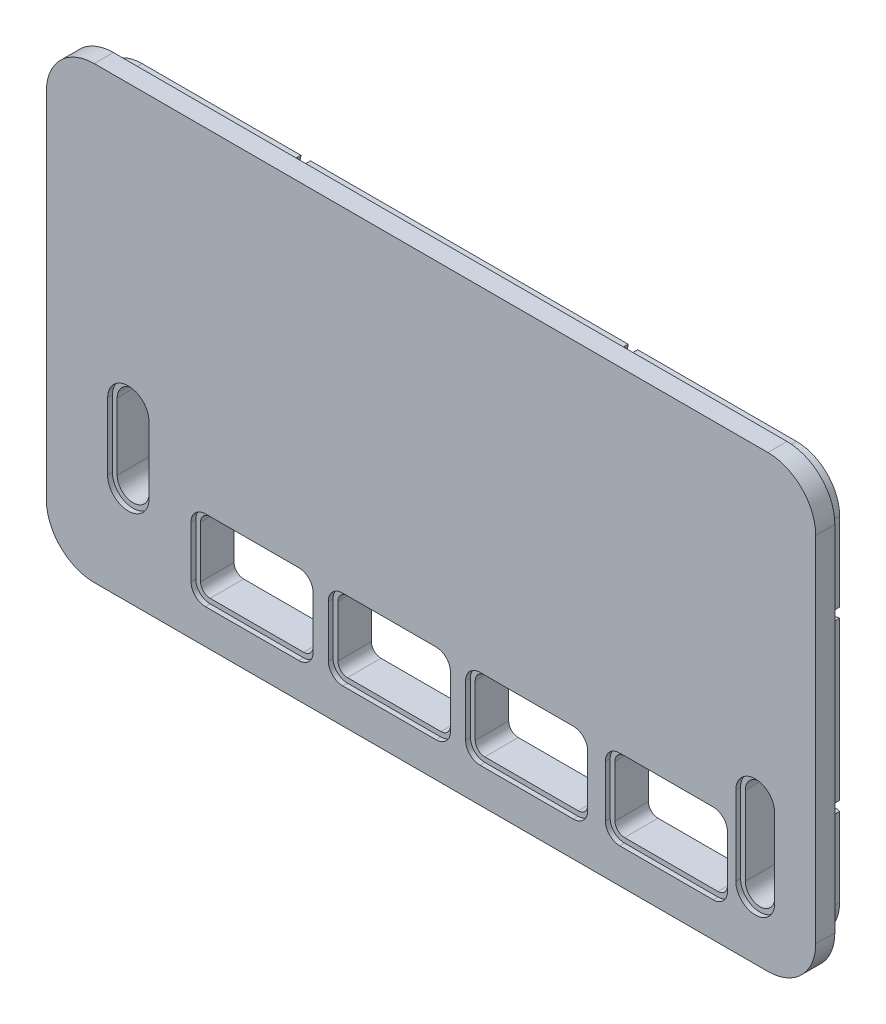
SolidWorks part; units mm, degrees
ref_plane "前视基准面" through (0, 0, 0) normal (0, 0, 1) x (1, 0, 0)
ref_plane "上视基准面" through (0, 0, 0) normal (0, 1, 0) x (1, 0, 0)
ref_plane "右视基准面" through (0, 0, 0) normal (1, 0, 0) x (0, 0, -1)
other "Configuration Table"
ref_plane "基准面1" through (0, 0, 994.7617) normal (0, 0, 1) x (1, 0, 0)
sketch "草图1" plane through (0, 0, 994.7617) normal (0, 0, 1) x (1, 0, 0)
  line L4 (-36.9772, -23.153) -> (-20.3758, -23.153)
  line L5 (35.9285, -18.653) -> (35.9285, -10.4094)
  line L6 (31.4285, 20.8216) -> (14.8271, 20.8216)
  line L7 (-41.4772, 16.3216) -> (-41.4772, 8.078)
  line L8 (-36.9772, -23.153) -> (-20.3758, -23.153)
  line L9 (35.9285, -18.653) -> (35.9285, -10.4094)
  line L10 (31.4285, 20.8216) -> (14.8271, 20.8216)
  line L11 (-41.4772, 16.3216) -> (-41.4772, 8.078)
  line L84 (35.9285, 8.078) -> (35.9285, 16.3216)
  line L85 (35.9285, 8.078) -> (35.9285, 16.3216)
  line L86 (-20.3758, 20.8216) -> (-36.9772, 20.8216)
  line L87 (-20.3758, 20.8216) -> (-36.9772, 20.8216)
  line L88 (-41.4772, -10.4094) -> (-41.4772, -18.653)
  line L89 (-41.4772, -10.4094) -> (-41.4772, -18.653)
  line L90 (14.8271, -23.153) -> (31.4285, -23.153)
  line L91 (14.8271, -23.153) -> (31.4285, -23.153)
  line L92 (15.3271, 19.8216) -> (13.3271, 19.8216)
  line L93 (15.3271, 19.8216) -> (13.3271, 19.8216)
  line L94 (13.8271, 20.8216) -> (-19.3758, 20.8216)
  line L95 (13.8271, 20.8216) -> (-19.3758, 20.8216)
  line L96 (-18.8758, 19.8216) -> (-20.8758, 19.8216)
  line L97 (-18.8758, 19.8216) -> (-20.8758, 19.8216)
  line L98 (-40.6203, 8.578) -> (-40.6203, 6.578)
  line L99 (-40.6203, 8.578) -> (-40.6203, 6.578)
  line L100 (-41.4772, 7.078) -> (-41.4772, -9.4094)
  line L101 (-41.4772, 7.078) -> (-41.4772, -9.4094)
  line L102 (-40.6203, -8.9094) -> (-40.6203, -10.9094)
  line L103 (-40.6203, -8.9094) -> (-40.6203, -10.9094)
  line L104 (-20.8758, -22.153) -> (-18.8758, -22.153)
  line L105 (-20.8758, -22.153) -> (-18.8758, -22.153)
  line L106 (-19.3758, -23.153) -> (13.8271, -23.153)
  line L107 (-19.3758, -23.153) -> (13.8271, -23.153)
  line L108 (13.3271, -22.153) -> (15.3271, -22.153)
  line L109 (13.3271, -22.153) -> (15.3271, -22.153)
  line L110 (35.0716, -10.9094) -> (35.0716, -8.9094)
  line L111 (35.0716, -10.9094) -> (35.0716, -8.9094)
  line L112 (35.9285, -9.4094) -> (35.9285, 7.078)
  line L113 (35.9285, -9.4094) -> (35.9285, 7.078)
  line L114 (35.0716, 6.578) -> (35.0716, 8.578)
  line L115 (35.0716, 6.578) -> (35.0716, 8.578)
  arc A4 (-41.4772, -18.653) -> (-36.9772, -23.153) centre (-36.9772, -18.653) ccw
  arc A5 (31.4285, -23.153) -> (35.9285, -18.653) centre (31.4285, -18.653) ccw
  arc A6 (35.9285, 16.3216) -> (31.4285, 20.8216) centre (31.4285, 16.3216) ccw
  arc A7 (-36.9772, 20.8216) -> (-41.4772, 16.3216) centre (-36.9772, 16.3216) ccw
  arc A8 (-41.4772, -18.653) -> (-36.9772, -23.153) centre (-36.9772, -18.653) ccw
  arc A9 (31.4285, -23.153) -> (35.9285, -18.653) centre (31.4285, -18.653) ccw
  arc A10 (35.9285, 16.3216) -> (31.4285, 20.8216) centre (31.4285, 16.3216) ccw
  arc A11 (-36.9772, 20.8216) -> (-41.4772, 16.3216) centre (-36.9772, 16.3216) ccw
  arc A84 (14.8271, 20.8216) -> (15.3271, 19.8216) centre (16.0771, 20.8216) ccw
  arc A85 (14.8271, 20.8216) -> (15.3271, 19.8216) centre (16.0771, 20.8216) ccw
  arc A86 (13.3271, 19.8216) -> (13.8271, 20.8216) centre (12.5771, 20.8216) ccw
  arc A87 (13.3271, 19.8216) -> (13.8271, 20.8216) centre (12.5771, 20.8216) ccw
  arc A88 (-19.3758, 20.8216) -> (-18.8758, 19.8216) centre (-18.1258, 20.8216) ccw
  arc A89 (-19.3758, 20.8216) -> (-18.8758, 19.8216) centre (-18.1258, 20.8216) ccw
  arc A90 (-20.8758, 19.8216) -> (-20.3758, 20.8216) centre (-21.6258, 20.8216) ccw
  arc A91 (-20.8758, 19.8216) -> (-20.3758, 20.8216) centre (-21.6258, 20.8216) ccw
  arc A92 (-41.4772, 8.078) -> (-40.6203, 8.578) centre (-41.1946, 8.578) ccw
  arc A93 (-41.4772, 8.078) -> (-40.6203, 8.578) centre (-41.1946, 8.578) ccw
  arc A94 (-40.6203, 6.578) -> (-41.4772, 7.078) centre (-41.4772, 6.0937) ccw
  arc A95 (-40.6203, 6.578) -> (-41.4772, 7.078) centre (-41.4772, 6.0937) ccw
  arc A96 (-41.4772, -9.4094) -> (-40.6203, -8.9094) centre (-41.4772, -8.4251) ccw
  arc A97 (-41.4772, -9.4094) -> (-40.6203, -8.9094) centre (-41.4772, -8.4251) ccw
  arc A98 (-40.6203, -10.9094) -> (-41.4772, -10.4094) centre (-41.1946, -10.9094) ccw
  arc A99 (-40.6203, -10.9094) -> (-41.4772, -10.4094) centre (-41.1946, -10.9094) ccw
  arc A100 (-20.3758, -23.153) -> (-20.8758, -22.153) centre (-21.6258, -23.153) ccw
  arc A101 (-20.3758, -23.153) -> (-20.8758, -22.153) centre (-21.6258, -23.153) ccw
  arc A102 (-18.8758, -22.153) -> (-19.3758, -23.153) centre (-18.1258, -23.153) ccw
  arc A103 (-18.8758, -22.153) -> (-19.3758, -23.153) centre (-18.1258, -23.153) ccw
  arc A104 (13.8271, -23.153) -> (13.3271, -22.153) centre (12.5771, -23.153) ccw
  arc A105 (13.8271, -23.153) -> (13.3271, -22.153) centre (12.5771, -23.153) ccw
  arc A106 (15.3271, -22.153) -> (14.8271, -23.153) centre (16.0771, -23.153) ccw
  arc A107 (15.3271, -22.153) -> (14.8271, -23.153) centre (16.0771, -23.153) ccw
  arc A108 (35.9285, -10.4094) -> (35.0716, -10.9094) centre (35.6459, -10.9094) ccw
  arc A109 (35.9285, -10.4094) -> (35.0716, -10.9094) centre (35.6459, -10.9094) ccw
  arc A110 (35.0716, -8.9094) -> (35.9285, -9.4094) centre (35.9285, -8.4251) ccw
  arc A111 (35.0716, -8.9094) -> (35.9285, -9.4094) centre (35.9285, -8.4251) ccw
  arc A112 (35.9285, 7.078) -> (35.0716, 6.578) centre (35.9285, 6.0937) ccw
  arc A113 (35.9285, 7.078) -> (35.0716, 6.578) centre (35.9285, 6.0937) ccw
  arc A114 (35.0716, 8.578) -> (35.9285, 8.078) centre (35.6459, 8.578) ccw
  arc A115 (35.0716, 8.578) -> (35.9285, 8.078) centre (35.6459, 8.578) ccw
  dimension "D1" = 0
extrude "凸台-拉伸1" add sketch "草图1" along normal blind 2
sketch "草图2" plane through (0, 0, 996.7617) normal (0, 0, 1) x (1, 0, 0)
  line L4 (-42.9772, 17.3216) -> (-42.9772, -19.653)
  line L5 (-37.9772, -24.653) -> (32.4285, -24.653)
  line L6 (37.4285, -19.653) -> (37.4285, 17.3216)
  line L7 (32.4285, 22.3216) -> (-37.9772, 22.3216)
  line L8 (-42.9772, 17.3216) -> (-42.9772, -19.653)
  line L9 (-37.9772, -24.653) -> (32.4285, -24.653)
  line L10 (37.4285, -19.653) -> (37.4285, 17.3216)
  line L11 (32.4285, 22.3216) -> (-37.9772, 22.3216)
  arc A4 (-37.9772, 22.3216) -> (-42.9772, 17.3216) centre (-37.9772, 17.3216) ccw
  arc A5 (-42.9772, -19.653) -> (-37.9772, -24.653) centre (-37.9772, -19.653) ccw
  arc A6 (32.4285, -24.653) -> (37.4285, -19.653) centre (32.4285, -19.653) ccw
  arc A7 (37.4285, 17.3216) -> (32.4285, 22.3216) centre (32.4285, 17.3216) ccw
  arc A8 (-37.9772, 22.3216) -> (-42.9772, 17.3216) centre (-37.9772, 17.3216) ccw
  arc A9 (-42.9772, -19.653) -> (-37.9772, -24.653) centre (-37.9772, -19.653) ccw
  arc A10 (32.4285, -24.653) -> (37.4285, -19.653) centre (32.4285, -19.653) ccw
  arc A11 (37.4285, 17.3216) -> (32.4285, 22.3216) centre (32.4285, 17.3216) ccw
  dimension "D1" = 0
extrude "凸台-拉伸2" add sketch "草图2" along normal blind 2
sketch "草图3" plane through (0, 0, 998.7617) normal (0, 0, 1) x (1, 0, 0)
  line L0 (-24.4898, -20.5208) -> (-18.4699, -20.5208)
  line L1 (-10.1388, -20.5208) -> (-4.1188, -20.5208)
  line L2 (4.2123, -20.5208) -> (10.2322, -20.5208)
  line L3 (18.8173, -20.5208) -> (24.8372, -20.5208)
  line L4 (-34.4109, -7.2326) -> (-34.4109, -14.2326) construction
  line L5 (-32.7459, -7.2326) -> (-32.7459, -14.2326)
  line L6 (-36.0759, -7.2326) -> (-36.0759, -14.2326)
  line L7 (31.1063, -9.9047) -> (31.1063, -18.1647) construction
  line L10 (32.6383, -9.9047) -> (32.6383, -18.1647)
  line L11 (29.5742, -9.9047) -> (29.5742, -18.1647)
  line L40 (-18.4699, -20.5208) -> (-16.5999, -20.5208)
  line L41 (-15.5999, -19.5208) -> (-15.5999, -14.1209)
  line L42 (-16.5999, -13.1209) -> (-26.3598, -13.1209)
  line L43 (-27.3598, -14.1209) -> (-27.3598, -19.5208)
  line L44 (-26.3598, -20.5208) -> (-24.4898, -20.5208)
  line L64 (-4.1188, -20.5208) -> (-2.2489, -20.5208)
  line L65 (-1.2489, -19.5208) -> (-1.2489, -14.1209)
  line L66 (-2.2489, -13.1209) -> (-12.0088, -13.1209)
  line L67 (-13.0088, -14.1209) -> (-13.0088, -19.5208)
  line L68 (-12.0088, -20.5208) -> (-10.1388, -20.5208)
  line L88 (10.2322, -20.5208) -> (12.1022, -20.5208)
  line L89 (13.1022, -19.5208) -> (13.1022, -14.1209)
  line L90 (12.1022, -13.1209) -> (2.3423, -13.1209)
  line L91 (1.3423, -14.1209) -> (1.3423, -19.5208)
  line L92 (2.3423, -20.5208) -> (4.2123, -20.5208)
  line L112 (24.8372, -20.5208) -> (26.7072, -20.5208)
  line L113 (27.7072, -19.5208) -> (27.7072, -14.1209)
  line L114 (26.7072, -13.1209) -> (16.9473, -13.1209)
  line L115 (15.9473, -14.1209) -> (15.9473, -19.5208)
  line L116 (16.9473, -20.5208) -> (18.8173, -20.5208)
  arc A0 (-32.7459, -7.2326) -> (-36.0759, -7.2326) centre (-34.4109, -7.2326) ccw
  arc A1 (-36.0759, -14.2326) -> (-32.7459, -14.2326) centre (-34.4109, -14.2326) ccw
  arc A4 (26.7072, -20.5208) -> (27.7072, -19.5208) centre (26.7072, -19.5208) ccw
  arc A5 (27.7072, -14.1209) -> (26.7072, -13.1209) centre (26.7072, -14.1209) ccw
  arc A6 (16.9473, -20.5208) -> (15.9473, -19.5208) centre (16.9473, -19.5208) cw
  arc A7 (16.9473, -13.1209) -> (15.9473, -14.1209) centre (16.9473, -14.1209) ccw
  arc A8 (13.1022, -14.1209) -> (12.1022, -13.1209) centre (12.1022, -14.1209) ccw
  arc A9 (12.1022, -20.5208) -> (13.1022, -19.5208) centre (12.1022, -19.5208) ccw
  arc A10 (1.3423, -19.5208) -> (2.3423, -20.5208) centre (2.3423, -19.5208) ccw
  arc A11 (1.3423, -14.1209) -> (2.3423, -13.1209) centre (2.3423, -14.1209) cw
  arc A12 (-1.2489, -14.1209) -> (-2.2489, -13.1209) centre (-2.2489, -14.1209) ccw
  arc A13 (-1.2489, -19.5208) -> (-2.2489, -20.5208) centre (-2.2489, -19.5208) cw
  arc A14 (-12.0088, -20.5208) -> (-13.0088, -19.5208) centre (-12.0088, -19.5208) cw
  arc A15 (-12.0088, -13.1209) -> (-13.0088, -14.1209) centre (-12.0088, -14.1209) ccw
  arc A16 (-16.5999, -20.5208) -> (-15.5999, -19.5208) centre (-16.5999, -19.5208) ccw
  arc A17 (-26.3598, -20.5208) -> (-27.3598, -19.5208) centre (-26.3598, -19.5208) cw
  arc A18 (-15.5999, -14.1209) -> (-16.5999, -13.1209) centre (-16.5999, -14.1209) ccw
  arc A19 (-27.3598, -14.1209) -> (-26.3598, -13.1209) centre (-26.3598, -14.1209) cw
  arc A24 (32.6383, -9.9047) -> (29.5742, -9.9047) centre (31.1063, -9.9047) ccw
  arc A25 (29.5742, -18.1647) -> (32.6383, -18.1647) centre (31.1063, -18.1647) ccw
  point P8 (-34.4109, -10.7326)
  point P18 (31.1063, -14.0347)
  dimension "D6" = 1
extrude "切除-拉伸2" cut sketch "草图3" against normal blind 4
sketch "草图6" plane through (0, 0, 998.7617) normal (0, 0, 1) x (1, 0, 0)
  line L8 (-27.8598, -14.1209) -> (-27.8598, -19.5208)
  line L9 (-26.3598, -21.0208) -> (-16.5999, -21.0208)
  line L10 (-15.0999, -19.5208) -> (-15.0999, -14.1209)
  line L11 (-16.5999, -12.6209) -> (-26.3598, -12.6209)
  line L12 (-27.8598, -14.1209) -> (-27.8598, -19.5208)
  line L13 (-26.3598, -21.0208) -> (-16.5999, -21.0208)
  line L14 (-15.0999, -19.5208) -> (-15.0999, -14.1209)
  line L15 (-16.5999, -12.6209) -> (-26.3598, -12.6209)
  line L20 (-0.7489, -19.5208) -> (-0.7489, -14.1209)
  line L21 (-12.0088, -21.0208) -> (-2.2489, -21.0208)
  line L22 (-13.5088, -14.1209) -> (-13.5088, -19.5208)
  line L23 (-2.2489, -12.6209) -> (-12.0088, -12.6209)
  line L24 (-0.7489, -19.5208) -> (-0.7489, -14.1209)
  line L25 (-12.0088, -21.0208) -> (-2.2489, -21.0208)
  line L26 (-13.5088, -14.1209) -> (-13.5088, -19.5208)
  line L27 (-2.2489, -12.6209) -> (-12.0088, -12.6209)
  line L32 (13.6022, -19.5208) -> (13.6022, -14.1209)
  line L33 (2.3423, -21.0208) -> (12.1022, -21.0208)
  line L34 (0.8423, -14.1209) -> (0.8423, -19.5208)
  line L35 (12.1022, -12.6209) -> (2.3423, -12.6209)
  line L36 (13.6022, -19.5208) -> (13.6022, -14.1209)
  line L37 (2.3423, -21.0208) -> (12.1022, -21.0208)
  line L38 (0.8423, -14.1209) -> (0.8423, -19.5208)
  line L39 (12.1022, -12.6209) -> (2.3423, -12.6209)
  line L44 (16.9473, -21.0208) -> (26.7072, -21.0208)
  line L45 (15.4473, -14.1209) -> (15.4473, -19.5208)
  line L46 (28.2072, -19.5208) -> (28.2072, -14.1209)
  line L47 (26.7072, -12.6209) -> (16.9473, -12.6209)
  line L48 (16.9473, -21.0208) -> (26.7072, -21.0208)
  line L49 (15.4473, -14.1209) -> (15.4473, -19.5208)
  line L50 (28.2072, -19.5208) -> (28.2072, -14.1209)
  line L51 (26.7072, -12.6209) -> (16.9473, -12.6209)
  line L52 (-36.5759, -7.2326) -> (-36.5759, -14.2326)
  line L53 (-32.2459, -14.2326) -> (-32.2459, -7.2326)
  line L54 (-36.5759, -7.2326) -> (-36.5759, -14.2326)
  line L55 (-32.2459, -14.2326) -> (-32.2459, -7.2326)
  line L62 (29.0742, -9.9047) -> (29.0742, -18.1647)
  line L63 (33.1383, -18.1647) -> (33.1383, -9.9047)
  line L64 (29.0742, -9.9047) -> (29.0742, -18.1647)
  line L65 (33.1383, -18.1647) -> (33.1383, -9.9047)
  arc A8 (-27.8598, -19.5208) -> (-26.3598, -21.0208) centre (-26.3598, -19.5208) ccw
  arc A9 (-16.5999, -21.0208) -> (-15.0999, -19.5208) centre (-16.5999, -19.5208) ccw
  arc A10 (-15.0999, -14.1209) -> (-16.5999, -12.6209) centre (-16.5999, -14.1209) ccw
  arc A11 (-26.3598, -12.6209) -> (-27.8598, -14.1209) centre (-26.3598, -14.1209) ccw
  arc A12 (-27.8598, -19.5208) -> (-26.3598, -21.0208) centre (-26.3598, -19.5208) ccw
  arc A13 (-16.5999, -21.0208) -> (-15.0999, -19.5208) centre (-16.5999, -19.5208) ccw
  arc A14 (-15.0999, -14.1209) -> (-16.5999, -12.6209) centre (-16.5999, -14.1209) ccw
  arc A15 (-26.3598, -12.6209) -> (-27.8598, -14.1209) centre (-26.3598, -14.1209) ccw
  arc A20 (-0.7489, -14.1209) -> (-2.2489, -12.6209) centre (-2.2489, -14.1209) ccw
  arc A21 (-2.2489, -21.0208) -> (-0.7489, -19.5208) centre (-2.2489, -19.5208) ccw
  arc A22 (-13.5088, -19.5208) -> (-12.0088, -21.0208) centre (-12.0088, -19.5208) ccw
  arc A23 (-12.0088, -12.6209) -> (-13.5088, -14.1209) centre (-12.0088, -14.1209) ccw
  arc A24 (-0.7489, -14.1209) -> (-2.2489, -12.6209) centre (-2.2489, -14.1209) ccw
  arc A25 (-2.2489, -21.0208) -> (-0.7489, -19.5208) centre (-2.2489, -19.5208) ccw
  arc A26 (-13.5088, -19.5208) -> (-12.0088, -21.0208) centre (-12.0088, -19.5208) ccw
  arc A27 (-12.0088, -12.6209) -> (-13.5088, -14.1209) centre (-12.0088, -14.1209) ccw
  arc A32 (13.6022, -14.1209) -> (12.1022, -12.6209) centre (12.1022, -14.1209) ccw
  arc A33 (12.1022, -21.0208) -> (13.6022, -19.5208) centre (12.1022, -19.5208) ccw
  arc A34 (0.8423, -19.5208) -> (2.3423, -21.0208) centre (2.3423, -19.5208) ccw
  arc A35 (2.3423, -12.6209) -> (0.8423, -14.1209) centre (2.3423, -14.1209) ccw
  arc A36 (13.6022, -14.1209) -> (12.1022, -12.6209) centre (12.1022, -14.1209) ccw
  arc A37 (12.1022, -21.0208) -> (13.6022, -19.5208) centre (12.1022, -19.5208) ccw
  arc A38 (0.8423, -19.5208) -> (2.3423, -21.0208) centre (2.3423, -19.5208) ccw
  arc A39 (2.3423, -12.6209) -> (0.8423, -14.1209) centre (2.3423, -14.1209) ccw
  arc A44 (26.7072, -21.0208) -> (28.2072, -19.5208) centre (26.7072, -19.5208) ccw
  arc A45 (15.4473, -19.5208) -> (16.9473, -21.0208) centre (16.9473, -19.5208) ccw
  arc A46 (28.2072, -14.1209) -> (26.7072, -12.6209) centre (26.7072, -14.1209) ccw
  arc A47 (16.9473, -12.6209) -> (15.4473, -14.1209) centre (16.9473, -14.1209) ccw
  arc A48 (26.7072, -21.0208) -> (28.2072, -19.5208) centre (26.7072, -19.5208) ccw
  arc A49 (15.4473, -19.5208) -> (16.9473, -21.0208) centre (16.9473, -19.5208) ccw
  arc A50 (28.2072, -14.1209) -> (26.7072, -12.6209) centre (26.7072, -14.1209) ccw
  arc A51 (16.9473, -12.6209) -> (15.4473, -14.1209) centre (16.9473, -14.1209) ccw
  arc A52 (-36.5759, -14.2326) -> (-32.2459, -14.2326) centre (-34.4109, -14.2326) ccw
  arc A53 (-32.2459, -7.2326) -> (-36.5759, -7.2326) centre (-34.4109, -7.2326) ccw
  arc A54 (-36.5759, -14.2326) -> (-32.2459, -14.2326) centre (-34.4109, -14.2326) ccw
  arc A55 (-32.2459, -7.2326) -> (-36.5759, -7.2326) centre (-34.4109, -7.2326) ccw
  arc A60 (29.0742, -18.1647) -> (33.1383, -18.1647) centre (31.1063, -18.1647) ccw
  arc A61 (33.1383, -9.9047) -> (29.0742, -9.9047) centre (31.1063, -9.9047) ccw
  arc A62 (29.0742, -18.1647) -> (33.1383, -18.1647) centre (31.1063, -18.1647) ccw
  arc A63 (33.1383, -9.9047) -> (29.0742, -9.9047) centre (31.1063, -9.9047) ccw
  dimension "D1" = 0.5
  dimension "D2" = 0.5
  dimension "D3" = 0.5
  dimension "D4" = 0.5
  dimension "D5" = 0.5
  dimension "D6" = 0.5
extrude "切除-拉伸3" cut sketch "草图6" against normal blind 0.5
